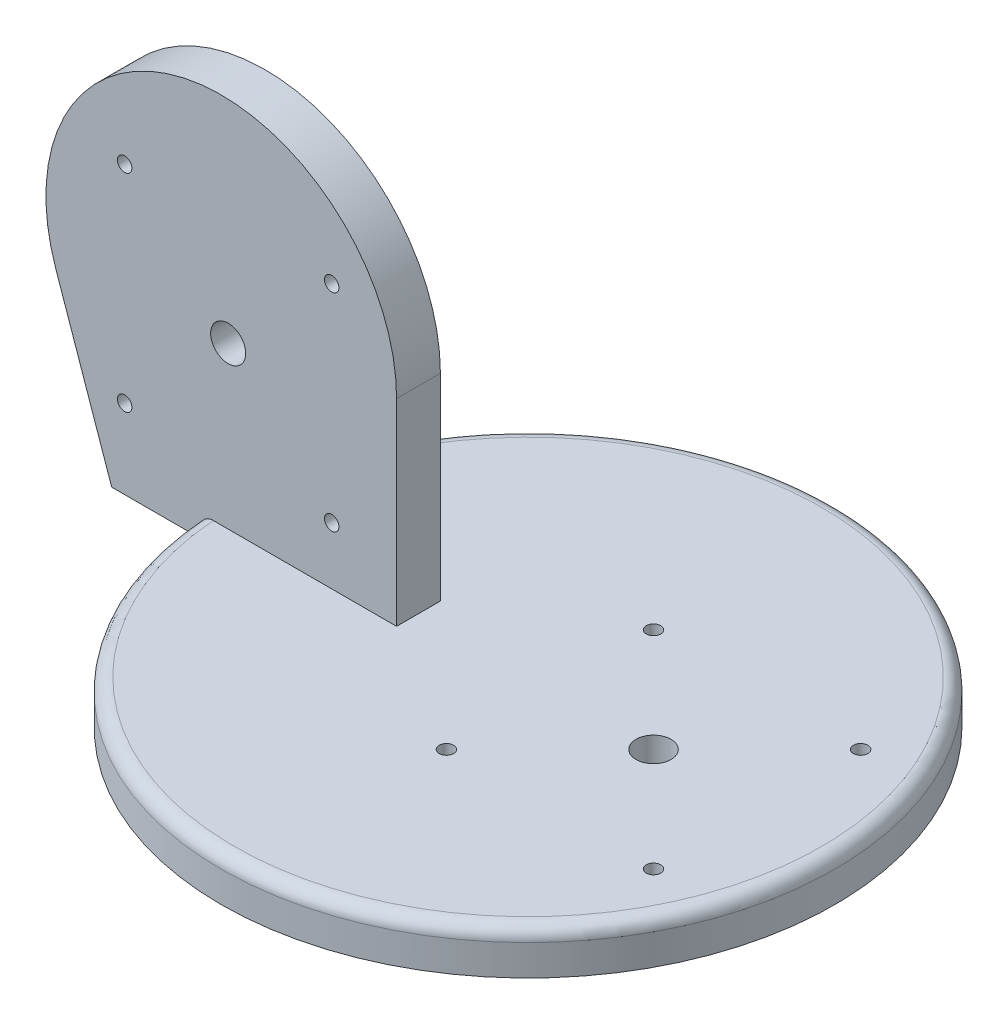
SolidWorks part; units mm, degrees
ref_plane "Front Plane" through (0, 0, 0) normal (0, 0, 1) x (1, 0, 0)
ref_plane "Top Plane" through (0, 0, 0) normal (0, 1, 0) x (1, 0, 0)
ref_plane "Right Plane" through (0, 0, 0) normal (1, 0, 0) x (0, 0, -1)
sketch "Sketch1" plane through (0, 0, 0) normal (0, 1, 0) x (1, 0, 0)
  circle A0 centre (0, 0) radius 70
  dimension "D1" = 140
extrude "Boss-Extrude1" add sketch "Sketch1" along normal blind 10
sketch "Sketch2" plane through (0, 0, 0) normal (0, -1, 0) x (1, 0, 0)
  circle A2 centre (0, 0) radius 65
  circle A3 centre (0, 0) radius 65
  dimension "D1" = 5
extrude "Boss-Extrude4" add sketch "Sketch2" along normal blind 3
sketch "Sketch3" plane through (0, 0, 0) normal (0, 0, 1) x (1, 0, 0)
  line L0 (-25, 55) -> (-25, 5)
  line L1 (-25, 5) -> (-90, 5)
  line L2 (-90, 5) -> (-102.7928, 41.8964)
  arc A0 (-102.7928, 41.8964) -> (-25, 55) centre (-65, 55) cw
  dimension "D3" = 40
  dimension "D1" = 25
  dimension "D2" = 5
  dimension "D4" = 65
  dimension "D5" = 50
extrude "Boss-Extrude5" add sketch "Sketch3" along normal mid plane 10
hole_wizard "M4x0.7 Tapped Hole1" positions "Sketch5" profile "Sketch6" tap size "M4x0.7" standard "ANSI Metric"
sketch "Sketch5" plane through (0, 10, 0) normal (0, 1, 0) x (1, 0, 0)
  point P0 (5, 23.622)
  point P2 (52.244, 23.622)
  point P4 (52.244, -23.622)
  point P6 (5, -23.622)
  dimension "D1" = 47.244
  dimension "D2" = 47.244
sketch "Sketch6" plane through (5, 10, -23.622) normal (1, 0, 0) x (0, 0, 1)
  line L0 (0, 0) -> (0, 6.9914)
  line L1 (0, 6.9914) -> (1.65, 6)
  line L2 (1.65, 6) -> (1.65, 0)
  line L5 (1.65, 0) -> (0, 0)
  line L10 (0, 6.9914) -> (-1.65, 6) construction
  line L11 (0, -6.35) -> (0, 107.95) construction
  dimension "Tap Drill Dia." = 3.3
  dimension "Tap Drill Depth" = 6
  dimension "Drill Angle" = 118
cosmetic thread "Hole Thread1" parameters "D1"=5, "D2"=4
cosmetic thread "Hole Thread2" parameters "D1"=5, "D2"=4
cosmetic thread "Hole Thread3" parameters "D1"=5, "D2"=4
cosmetic thread "Hole Thread4" parameters "D1"=5, "D2"=4
hole_wizard "Ø8.0mm Dowel Hole2" positions "Sketch9" profile "Sketch10" hole size "Ø8.0" standard "ANSI Metric" end condition through all
sketch "Sketch9" plane through (0, 0, -5) normal (0, 0, -1) x (1, 0, 0)
  point P0 (-63.4203, -46.697)
sketch "Sketch10" plane through (-63.4203, 46.697, -5) normal (1, 0, 0) x (0, 1, 0)
  line L0 (0, 0) -> (0, 75)
  line L1 (0, 75) -> (4, 75)
  line L2 (4, 75) -> (4, 0)
  line L5 (4, 0) -> (0, 0)
  line L11 (0, -6.35) -> (0, 107.95) construction
  dimension "Thru Hole Dia." = 8
  dimension "Thru Hole Depth" = 75
hole_wizard "M4x0.7 Tapped Hole3" positions "Sketch15" profile "Sketch16" tap size "M4x0.7" standard "ANSI Metric"
sketch "Sketch15" plane through (0, 0, 5) normal (0, 0, 1) x (1, 0, 0)
  circle A0 centre (-63.4203, 46.697) radius 4 construction
  point P0 (-87.0403, 70.317)
  point P2 (-39.8003, 70.317)
  point P4 (-39.8003, 23.077)
  point P6 (-87.0403, 23.077)
  dimension "D1" = 47.24
  dimension "D2" = 47.24
  dimension "D3" = 23.62
  dimension "D4" = 23.62
sketch "Sketch16" plane through (-87.0403, 70.317, 5) normal (1, 0, 0) x (0, -1, 0)
  line L0 (0, 0) -> (0, 6.9914)
  line L1 (0, 6.9914) -> (1.65, 6)
  line L2 (1.65, 6) -> (1.65, 0)
  line L5 (1.65, 0) -> (0, 0)
  line L10 (0, 6.9914) -> (-1.65, 6) construction
  line L11 (0, -6.35) -> (0, 107.95) construction
  dimension "Tap Drill Dia." = 3.3
  dimension "Tap Drill Depth" = 6
  dimension "Drill Angle" = 118
cosmetic thread "Hole Thread9" parameters "D1"=5, "D2"=4
cosmetic thread "Hole Thread10" parameters "D1"=5, "D2"=4
cosmetic thread "Hole Thread11" parameters "D1"=5, "D2"=4
cosmetic thread "Hole Thread12" parameters "D1"=5, "D2"=4
hole_wizard "Ø8.0mm Dowel Hole3" positions "Sketch17" profile "Sketch18" hole size "Ø8.0" standard "ANSI Metric" end condition through all
sketch "Sketch17" plane through (0, 10, 0) normal (0, 1, 0) x (1, 0, 0)
  circle A1 centre (52.244, 23.622) radius 1.65 construction
  circle A2 centre (52.244, -23.622) radius 1.65 construction
  point P0 (28.624, -0.002)
  dimension "D1" = 23.62
  dimension "D2" = 23.62
sketch "Sketch18" plane through (28.624, 10, 0.002) normal (1, 0, 0) x (0, 0, 1)
  line L0 (0, 0) -> (0, 13)
  line L1 (0, 13) -> (4, 13)
  line L2 (4, 13) -> (4, 0)
  line L5 (4, 0) -> (0, 0)
  line L11 (0, -6.35) -> (0, 107.95) construction
  dimension "Thru Hole Dia." = 8
  dimension "Thru Hole Depth" = 13
fillet "Fillet1" radius 3 1 edges at (70, 10, 0)
